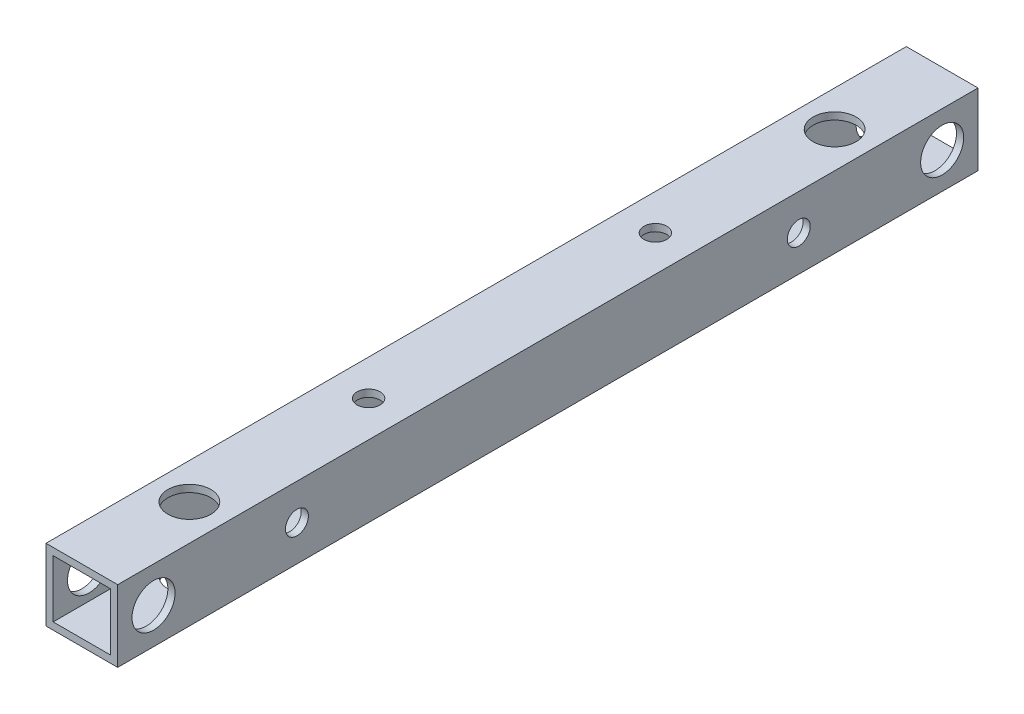
SolidWorks part; units mm, degrees
ref_plane "正面" through (0, 0, 0) normal (0, 0, 1) x (1, 0, 0)
ref_plane "平面" through (0, 0, 0) normal (0, 1, 0) x (1, 0, 0)
ref_plane "右側面" through (0, 0, 0) normal (1, 0, 0) x (0, 0, -1)
sketch "ｽｹｯﾁ1" plane through (0, 0, 0) normal (0, 0, 1) x (1, 0, 0)
  line L5 (-5, -5) -> (5, -5)
  line L6 (-5, -5) -> (-5, 5)
  line L7 (-5, 5) -> (5, 5)
  line L8 (5, -5) -> (5, 5)
  line L9 (-5, -5) -> (5, 5) construction
  line L10 (-5, 5) -> (5, -5) construction
  line L11 (4, -4) -> (-4, -4)
  line L12 (4, -4) -> (4, 4)
  line L13 (4, 4) -> (-4, 4)
  line L14 (-4, -4) -> (-4, 4)
  line L15 (4, -4) -> (-4, 4) construction
  line L16 (4, 4) -> (-4, -4) construction
  point P0 (0, 0)
  point P7 (0, 0)
  dimension "D1" = 10
  dimension "D2" = 10
  dimension "D3" = 8
extrude "ﾎﾞｽ - 押し出し1" add sketch "ｽｹｯﾁ1" along normal blind 120
sketch "ｽｹｯﾁ2" plane through (-5, 0, 0) normal (-1, 0, 0) x (0, 0, 1)
  line L0 (0, 5) -> (0, -5) construction
  line L1 (120, -5) -> (0, -5) construction
  line L2 (120, 5) -> (120, -5) construction
  circle A0 centre (5, 0) radius 3
  circle A1 centre (115, 0) radius 3
  dimension "D1" = 6
  dimension "D2" = 6
  dimension "D3" = 5
  dimension "D4" = 5
  dimension "D5" = 5
  dimension "D6" = 5
extrude "ｶｯﾄ - 押し出し1" cut sketch "ｽｹｯﾁ2" against normal through all
sketch "ｽｹｯﾁ3" plane through (0, 5, 0) normal (0, 1, 0) x (1, 0, 0)
  line L0 (5, -120) -> (-5, -120) construction
  line L1 (5, -120) -> (5, 0) construction
  line L2 (5, 0) -> (-5, 0) construction
  line L3 (-5, -120) -> (-5, 0) construction
  circle A0 centre (0, -105) radius 3
  circle A1 centre (0, -15) radius 3
  dimension "D1" = 6
  dimension "D2" = 15
  dimension "D3" = 5
  dimension "D4" = 6
  dimension "D5" = 15
  dimension "D6" = 5
extrude "ｶｯﾄ - 押し出し2" cut sketch "ｽｹｯﾁ3" against normal blind 10
sketch "ｽｹｯﾁ4" plane through (0, 5, 0) normal (0, 1, 0) x (1, 0, 0)
  line L0 (-5, -120) -> (-5, 0) construction
  circle A0 centre (0, -40) radius 1.6
  circle A1 centre (0, -80) radius 1.6
  circle A2 centre (0, -15) radius 3 construction
  circle A3 centre (0, -105) radius 3 construction
  dimension "D1" = 3.2
  dimension "D2" = 3.2
  dimension "D3" = 25
  dimension "D4" = 25
  dimension "D5" = 5
  dimension "D6" = 5
extrude "ｶｯﾄ - 押し出し3" cut sketch "ｽｹｯﾁ4" against normal blind 10
sketch "ｽｹｯﾁ5" plane through (-5, 0, 0) normal (-1, 0, 0) x (0, 0, 1)
  line L0 (120, -5) -> (0, -5) construction
  line L1 (120, 5) -> (0, 5) construction
  circle A0 centre (25, 0) radius 1.6
  circle A1 centre (95, 0) radius 1.6
  circle A2 centre (5, 0) radius 3 construction
  circle A3 centre (115, 0) radius 3 construction
  dimension "D1" = 3.2
  dimension "D2" = 20
  dimension "D3" = 5
  dimension "D4" = 3.2
  dimension "D5" = 5
  dimension "D6" = 20
extrude "ｶｯﾄ - 押し出し4" cut sketch "ｽｹｯﾁ5" against normal through all
sketch "ｽｹｯﾁ6" plane through (0, -5, 0) normal (0, -1, 0) x (-1, 0, 0)
  circle A0 centre (0, -40) radius 3
  circle A1 centre (0, -80) radius 3
  dimension "D1" = 6
  dimension "D2" = 6
extrude "ｶｯﾄ - 押し出し5" cut sketch "ｽｹｯﾁ6" against normal blind 2
